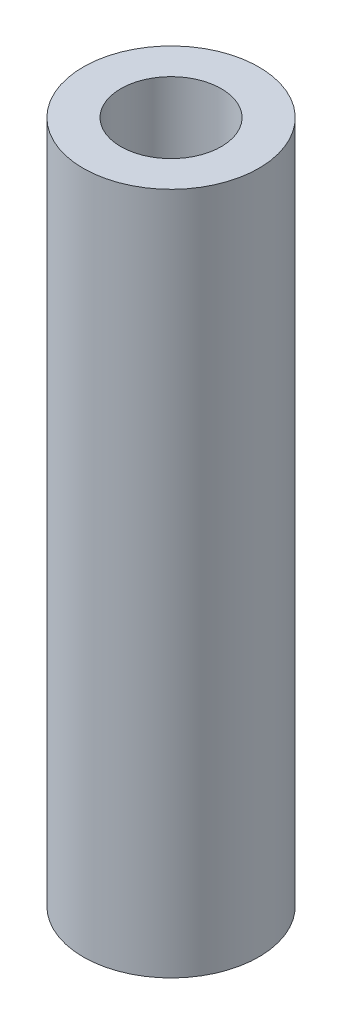
SolidWorks part; units mm, degrees
ref_plane "前视基准面" through (0, 0, 0) normal (0, 0, 1) x (1, 0, 0)
ref_plane "上视基准面" through (0, 0, 0) normal (0, 1, 0) x (1, 0, 0)
ref_plane "右视基准面" through (0, 0, 0) normal (1, 0, 0) x (0, 0, -1)
sketch "草图1" plane through (0, 0, 0) normal (0, 1, 0) x (1, 0, 0)
  circle A0 centre (0, 0) radius 4.5
  circle A1 centre (0, 0) radius 2.575
  dimension "D1" = 5.15
  dimension "D2" = 9
extrude "凸台-拉伸1" add sketch "草图1" along normal blind 35
